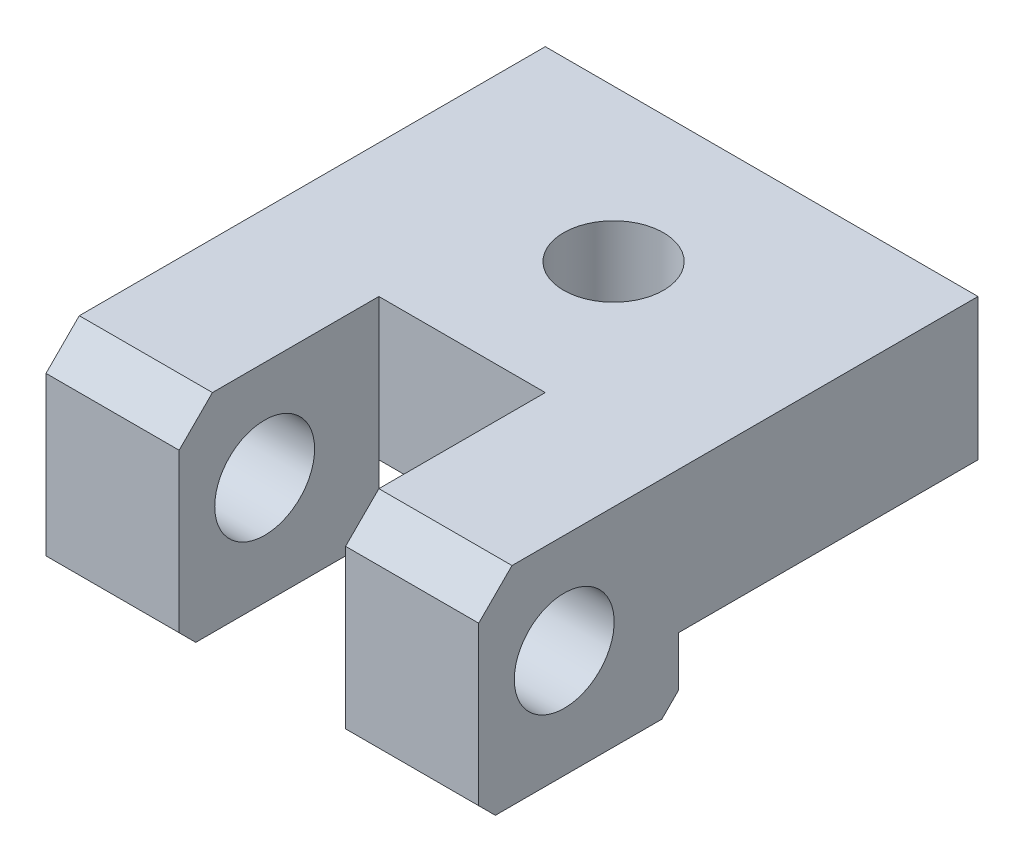
SolidWorks part; units mm, degrees
ref_plane "Спереди" through (0, 0, 0) normal (0, 0, 1) x (1, 0, 0)
ref_plane "Сверху" through (0, 0, 0) normal (0, 1, 0) x (1, 0, 0)
ref_plane "Справа" through (0, 0, 0) normal (1, 0, 0) x (0, 0, -1)
sketch "Эскиз1" plane through (0, 0, 0) normal (0, 0, 1) x (1, 0, 0)
  line L1 (-15, 6) -> (15, 6)
  line L2 (-15, 6) -> (-15, -7.5)
  line L3 (-15, -7.5) -> (15, -7.5)
  line L4 (15, 6) -> (15, -7.5)
extrude "Вытянуть1" add sketch "Эскиз1" along normal blind 20
sketch "Эскиз2" plane through (0, -7.5, 0) normal (0, -1, 0) x (1, 0, 0)
  line L0 (0, 21.5367) -> (0, 9.7512) construction
  line L2 (-15, 0) -> (15, 0) construction
  line L3 (-5, 28.1632) -> (5, 28.1632)
  line L4 (-5, 28.1632) -> (-5, 8)
  line L5 (-5, 8) -> (5, 8)
  line L6 (5, 28.1632) -> (5, 8)
  line L7 (-5, 28.1632) -> (5, 8) construction
  line L8 (-5, 8) -> (5, 28.1632) construction
  point P1 (0, 18.0816)
  dimension "D1" = 8
extrude "Вытянуть2" cut sketch "Эскиз2" against normal through all
sketch "Эскиз3" plane through (15, 0, 0) normal (1, 0, 0) x (0, 0, -1)
  circle A0 centre (-14.8614, 0) radius 3
extrude "Вытянуть3" cut sketch "Эскиз3" against normal through all
sketch "Эскиз6" plane through (0, 0, 0) normal (0, 0, -1) x (-1, 0, 0)
  line L0 (-15, 6) -> (15, 6) construction
  line L1 (15, 6) -> (-15, 6)
  line L2 (15, 6) -> (15, -7.5)
  line L3 (15, -7.5) -> (-15, -7.5)
  line L4 (-15, 6) -> (-15, -7.5)
extrude "Вытянуть5" add sketch "Эскиз6" along normal blind 10
sketch "Эскиз7" plane through (0, 6, 0) normal (0, 1, 0) x (1, 0, 0)
  circle A0 centre (0.2314, 0.8699) radius 3
extrude "Вырез-Вытянуть1" cut sketch "Эскиз7" against normal through all
sketch "Эскиз8" plane through (0, -7.5, 0) normal (0, -1, 0) x (1, 0, 0)
  line L0 (15, 20) -> (15, -10) construction
  line L1 (-15, -10) -> (15, -10)
  line L2 (-15, -10) -> (-15, 8)
  line L3 (-15, 8) -> (15, 8)
  line L4 (15, -10) -> (15, 8)
extrude "Вырез-Вытянуть2" cut sketch "Эскиз8" against normal blind 5
chamfer "Фаска1" distance 2 angle 45 6 edges at (10, 6, 20) (10, -7.5, 20) (-10, 6, 20) (-10, -7.5, 20) (-10, -7.5, 8) (10, -7.5, 8)
sketch "Эскиз9" plane through (0, 6, 0) normal (0, 1, 0) x (1, 0, 0)
  line L0 (0, 10) -> (0, 20.7943) construction
  line L2 (-13, 17.424) -> (-13, 0.1349) construction
  line L3 (-15, -18) -> (-15, 10) construction
  line L4 (13, 13.3999) -> (13, -20.0583)
  line L5 (-19.524, 13.3999) -> (-13, 13.3999)
  line L6 (-19.524, 13.3999) -> (-19.524, -20.0583)
  line L7 (-19.524, -20.0583) -> (-13, -20.0583)
  line L8 (-13, 13.3999) -> (-13, -20.0583)
  line L9 (19.524, -20.0583) -> (13, -20.0583)
  line L10 (19.524, 13.3999) -> (19.524, -20.0583)
  line L11 (19.524, 13.3999) -> (13, 13.3999)
  dimension "D1" = 2
extrude "Вытянуть6" cut sketch "Эскиз9" against normal through all
sketch "Эскиз14" plane through (0, -7.5, 0) normal (0, -1, 0) x (1, 0, 0)
  line L1 (42.5138, 22.154) -> (-42.3901, 22.154)
  line L2 (42.5138, 22.154) -> (42.5138, -22.8093)
  line L3 (42.5138, -22.8093) -> (-42.3901, -22.8093)
  line L4 (-42.3901, 22.154) -> (-42.3901, -22.8093)
extrude "Вытянуть10" cut sketch "Эскиз14" against normal blind 1
sketch "Эскиз15" plane through (0, 0, -10) normal (0, 0, -1) x (-1, 0, 0)
  circle A0 centre (-8, 1.7485) radius 2
  circle A1 centre (8, 1.75) radius 2
extrude "Вырез-Вытянуть3" cut sketch "Эскиз15" against normal blind 16
